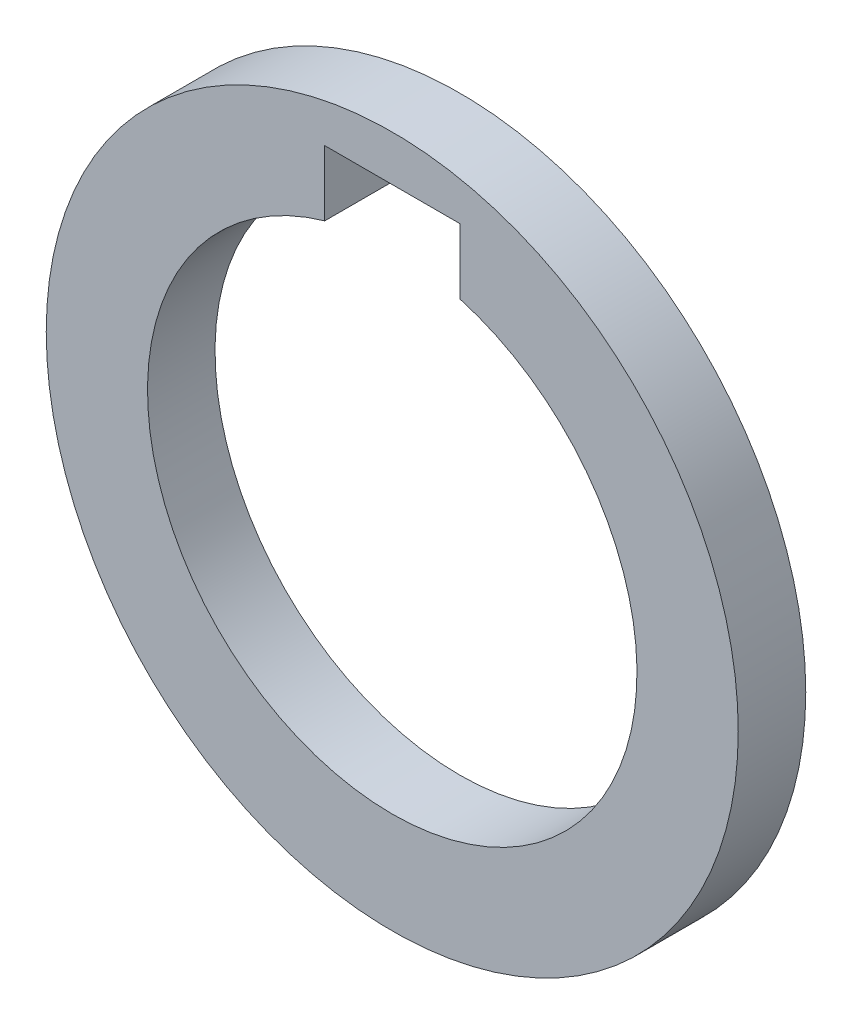
SolidWorks part; units mm, degrees
ref_plane "前视基准面" through (0, 0, 0) normal (0, 0, 1) x (1, 0, 0)
ref_plane "上视基准面" through (0, 0, 0) normal (0, 1, 0) x (1, 0, 0)
ref_plane "右视基准面" through (0, 0, 0) normal (1, 0, 0) x (0, 0, -1)
other "Configuration Table"
sketch "草图1" plane through (0, 0, 0) normal (0, 0, 1) x (1, 0, 0)
  line L0 (0, 0) -> (0, 26.2989) construction
  line L1 (-4, 13.9374) -> (-4, 17.8)
  line L2 (-4, 17.8) -> (4, 17.8)
  line L3 (4, 17.8) -> (4, 13.9374)
  circle A0 centre (0, 0) radius 20.5
  arc A1 (-4, 13.9374) -> (4, 13.9374) centre (0, 0) ccw
  dimension "D1" = 41
  dimension "D2" = 29
  dimension "D3" = 8
  dimension "D4" = 32.3
extrude "凸台-拉伸1" add sketch "草图1" along normal blind 4
